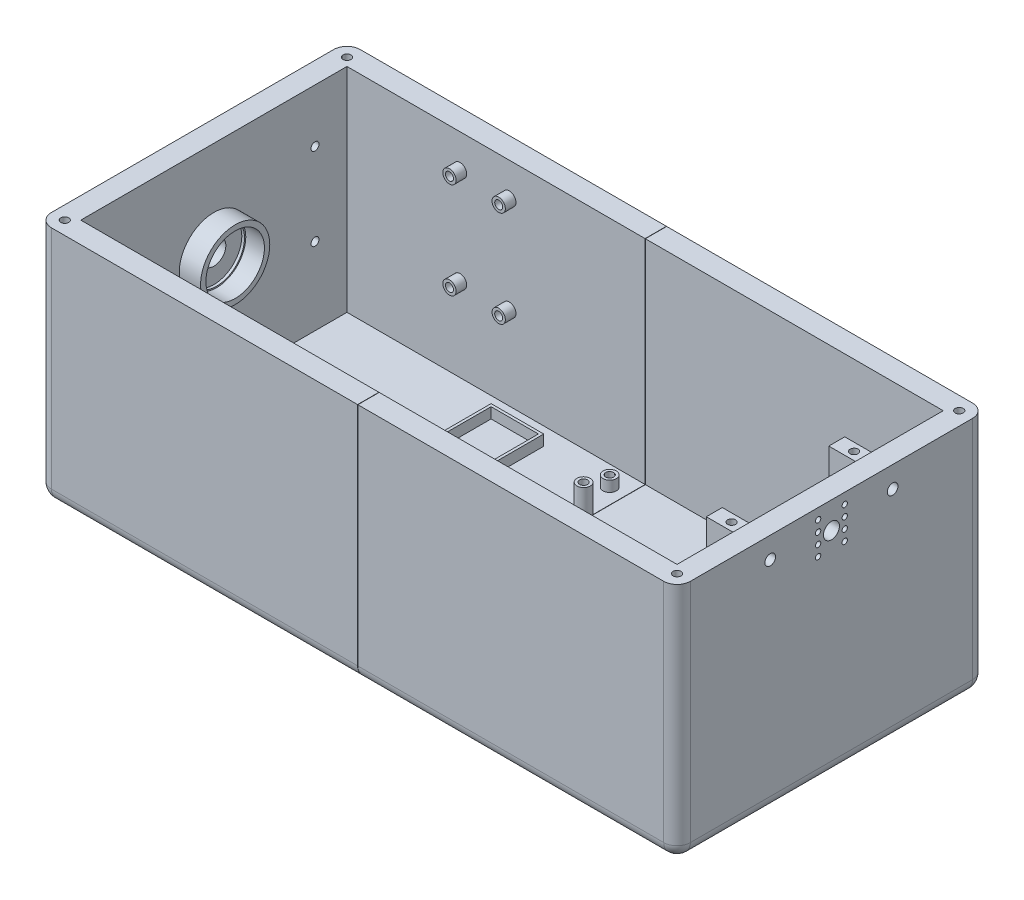
SolidWorks part; units mm, degrees
ref_plane "Front Plane" through (0, 0, 0) normal (0, 0, 1) x (1, 0, 0)
ref_plane "Top Plane" through (0, 0, 0) normal (0, 1, 0) x (1, 0, 0)
ref_plane "Right Plane" through (0, 0, 0) normal (1, 0, 0) x (0, 0, -1)
sketch "Sketch1" plane through (0, 0, 0) normal (0, 1, 0) x (1, 0, 0)
  line L1 (-120, 58) -> (120, 58)
  line L2 (-120, 58) -> (-120, -58)
  line L3 (-120, -58) -> (120, -58)
  line L4 (120, 58) -> (120, -58)
  line L5 (-120, 58) -> (120, -58) construction
  line L6 (-120, -58) -> (120, 58) construction
  point P0 (0, 0)
  dimension "D1" = 240
  dimension "D2" = 116
extrude "Boss-Extrude1" add sketch "Sketch1" along normal blind 10
sketch "Sketch2" plane through (0, 0, 0) normal (0, -1, 0) x (1, 0, 0)
  line L1 (-31.075, 31.075) -> (31.075, 31.075)
  line L2 (-31.075, 31.075) -> (-31.075, -31.075)
  line L3 (-31.075, -31.075) -> (31.075, -31.075)
  line L4 (31.075, 31.075) -> (31.075, -31.075)
  line L5 (-31.075, 31.075) -> (31.075, -31.075) construction
  line L6 (-31.075, -31.075) -> (31.075, 31.075) construction
  point P0 (0, 0)
  dimension "D1" = 62.15
  dimension "D2" = 62.15
extrude "Cut-Extrude1" cut sketch "Sketch2" against normal blind 2.5
sketch "Sketch3" plane through (0, 2.5, 0) normal (0, -1, 0) x (1, 0, 0)
  line L0 (0, 31.075) -> (0, -31.075) construction
  line L1 (31.075, 31.075) -> (-31.075, 31.075) construction
  line L2 (-31.075, -31.075) -> (31.075, -31.075) construction
  line L3 (-31.075, 0) -> (31.075, 0) construction
  line L4 (-31.075, 31.075) -> (-31.075, -31.075) construction
  line L5 (31.075, -31.075) -> (31.075, 31.075) construction
  line L6 (31.075, 31.075) -> (-31.075, 31.075) construction
  line L7 (-31.075, 31.075) -> (-31.075, -31.075) construction
  circle A0 centre (-26.075, 26.075) radius 1.5
  circle A1 centre (-26.075, -26.075) radius 1.5
  circle A2 centre (26.075, -26.075) radius 1.5
  circle A3 centre (26.075, 26.075) radius 1.5
  dimension "D1" = 3
  dimension "D3" = 5
  dimension "D2" = 5
extrude "Cut-Extrude2" cut sketch "Sketch3" against normal up to next
sketch "Sketch4" plane through (0, 0, 0) normal (0, -1, 0) x (1, 0, 0)
  line L0 (120, 58) -> (120, -58) construction
  line L1 (48, 7.75) -> (60, 7.75)
  line L2 (48, 7.75) -> (48, -7.75)
  line L3 (48, -7.75) -> (60, -7.75)
  line L4 (60, 7.75) -> (60, -7.75)
  line L5 (48, 7.75) -> (60, -7.75) construction
  line L6 (48, -7.75) -> (60, 7.75) construction
  point P0 (54, 0)
  dimension "D1" = 12
  dimension "D2" = 15.5
  dimension "D3" = 60
extrude "Cut-Extrude3" cut sketch "Sketch4" against normal blind 2.5
sketch "Sketch6" plane through (0, 2.5, 0) normal (0, -1, 0) x (1, 0, 0)
  line L0 (60, -7.75) -> (60, 7.75) construction
  line L1 (60, 7.75) -> (48, 7.75) construction
  line L2 (48, -7.75) -> (60, -7.75) construction
  circle A0 centre (58, 5.75) radius 1.5
  circle A1 centre (58, -5.75) radius 1.5
  dimension "D1" = 3
  dimension "D2" = 3
  dimension "D3" = 2
  dimension "D4" = 2
  dimension "D5" = 2
  dimension "D6" = 2
extrude "Cut-Extrude4" cut sketch "Sketch6" against normal up to next and the other way through all
sketch "Sketch7" plane through (0, 2.5, 0) normal (0, -1, 0) x (1, 0, 0)
  line L0 (48, -7.75) -> (60, -7.75) construction
  line L1 (48, 7.75) -> (54, 7.75)
  line L2 (48, 7.75) -> (48, -7.75)
  line L3 (48, -7.75) -> (54, -7.75)
  line L4 (54, 7.75) -> (54, -7.75)
extrude "Cut-Extrude5" cut sketch "Sketch7" against normal up to next
sketch "Sketch8" plane through (0, 10, 0) normal (0, 1, 0) x (1, 0, 0)
  line L1 (1.2, 26.7) -> (100, 26.7) construction
  line L2 (1.2, 26.7) -> (1.2, -26.7) construction
  line L3 (1.2, -26.7) -> (100, -26.7) construction
  line L4 (100, 26.7) -> (100, -26.7) construction
  line L5 (1.2, 26.7) -> (100, -26.7) construction
  line L6 (1.2, -26.7) -> (100, 26.7) construction
  line L11 (120, -58) -> (120, 58) construction
  line L15 (-120, -58) -> (120, -58) construction
  circle A0 centre (2.7, 24.2) radius 1.5
  circle A1 centre (9.7, -24.2) radius 1.5
  circle A2 centre (86.5, 24.2) radius 1.5
  circle A3 centre (84.5, -24.2) radius 1.5
  circle A4 centre (86.5, 24.2) radius 2.5
  circle A5 centre (84.5, -24.2) radius 2.3473
  circle A6 centre (9.7, -24.2) radius 2.5
  circle A7 centre (2.7, 24.2) radius 2.5
  point P0 (50.6, 0)
  dimension "D7" = 3
  dimension "D8" = 3
  dimension "D9" = 3
  dimension "D10" = 3
  dimension "D11" = 2.5
  dimension "D13" = 8.5
  dimension "D14" = 2.5
  dimension "D12" = 15.5
  dimension "D16" = 13.5
  dimension "D17" = 2.5
  dimension "D18" = 5
  dimension "D19" = 5
  dimension "D20" = 5
  dimension "D1" = 98.8
  dimension "D2" = 53.4
  dimension "D3" = 20
  dimension "D4" = 58
  dimension "D15" = 2.5
extrude "Boss-Extrude2" add sketch "Sketch8" along normal blind 15
sketch "Sketch9" plane through (0, 10, 0) normal (0, 1, 0) x (1, 0, 0)
  line L0 (-0.3, 58) -> (-0.3, -58) construction
  line L1 (-25.6, 47) -> (-4.3, 47) construction
  line L2 (-25.6, 47) -> (-25.6, 8.5) construction
  line L3 (-25.6, 8.5) -> (-4.3, 8.5) construction
  line L4 (-4.3, 47) -> (-4.3, 8.5) construction
  line L5 (-25.6, 47) -> (-4.3, 8.5) construction
  line L6 (-25.6, 8.5) -> (-4.3, 47) construction
  line L7 (-53.1, 47) -> (-29.6, 47) construction
  line L8 (-53.1, 47) -> (-53.1, 5) construction
  line L9 (-53.1, 5) -> (-29.6, 5) construction
  line L10 (-29.6, 47) -> (-29.6, 5) construction
  line L11 (-53.1, 47) -> (-29.6, 5) construction
  line L12 (-53.1, 5) -> (-29.6, 47) construction
  line L13 (120, 58) -> (-120, 58) construction
  line L14 (-120, -58) -> (120, -58) construction
  line L15 (-76.2, -9.5) -> (-54.9, -9.5) construction
  line L16 (-103.7, -9) -> (-80.2, -9) construction
  line L17 (-17.7, -47) -> (-17.7, -48)
  line L18 (-21.7, -23.8) -> (-4.3, -23.8)
  line L19 (-21.7, -23.8) -> (-21.7, -47)
  line L20 (-21.7, -47) -> (-17.7, -47)
  line L21 (-4.3, -23.8) -> (-4.3, -47)
  line L22 (-21.7, -23.8) -> (-4.3, -47) construction
  line L23 (-21.7, -47) -> (-4.3, -23.8) construction
  line L24 (-22.7, -22.8) -> (-3.3, -22.8)
  line L25 (-22.7, -22.8) -> (-22.7, -48)
  line L26 (-22.7, -48) -> (-17.7, -48)
  line L27 (-3.3, -22.8) -> (-3.3, -48)
  line L28 (-22.7, -22.8) -> (-3.3, -48) construction
  line L29 (-22.7, -48) -> (-3.3, -22.8) construction
  line L30 (-8.3, -47) -> (-8.3, -48)
  line L31 (-8.3, -47) -> (-4.3, -47)
  line L32 (-8.3, -48) -> (-3.3, -48)
  line L51 (-31.46, 43.383) -> (-31.46, 8.617)
  line L52 (-50.24, 42.383) -> (-32.46, 42.383)
  line L53 (-50.24, 42.383) -> (-50.24, 9.617)
  line L54 (-50.24, 9.617) -> (-32.46, 9.617)
  line L67 (31.45, 58) -> (31.45, -58) construction
  line L102 (-32.46, 42.383) -> (-32.46, 9.617)
  line L103 (-50.24, 42.383) -> (-32.46, 9.617) construction
  line L104 (-50.24, 9.617) -> (-32.46, 42.383) construction
  line L105 (-51.24, 8.617) -> (-31.46, 8.617)
  line L106 (-51.24, 43.383) -> (-51.24, 8.617)
  line L107 (-51.24, 43.383) -> (-31.46, 43.383)
  circle A0 centre (2.7, 24.2) radius 1.5 construction
  circle A1 centre (-5.8, 42.5) radius 1.5
  circle A2 centre (-5.8, 15.8) radius 1.5
  circle A3 centre (-24.1, 15.8) radius 1.5
  circle A4 centre (-24.1, 15.8) radius 2.5
  circle A5 centre (-5.8, 15.8) radius 2.5
  circle A6 centre (-5.8, 42.5) radius 2.5
  circle A7 centre (-50.6, 44.5) radius 1.5 construction
  circle A8 centre (-32.1, 44.5) radius 1.5 construction
  circle A9 centre (-32.1, 7.5) radius 1.5 construction
  circle A10 centre (-50.6, 7.5) radius 1.5 construction
  circle A11 centre (-50.6, 7.5) radius 2.5 construction
  circle A12 centre (-32.1, 7.5) radius 2.5 construction
  circle A13 centre (-32.1, 44.5) radius 2.5 construction
  circle A14 centre (-50.6, 44.5) radius 2.5 construction
  point P0 (-14.95, 27.75)
  point P5 (-41.35, 26)
  point P20 (-13, -35.4)
  point P27 (-13, -35.4)
  point P53 (-41.35, 26)
  dimension "D23" = 3
  dimension "D24" = 3
  dimension "D25" = 3
  dimension "D28" = 5
  dimension "D29" = 5
  dimension "D30" = 5
  dimension "D31" = 3
  dimension "D32" = 3
  dimension "D33" = 3
  dimension "D34" = 3
  dimension "D43" = 5
  dimension "D44" = 5
  dimension "D45" = 5
  dimension "D46" = 5
  dimension "D1" = 38.5
  dimension "D2" = 21.3
  dimension "D3" = 3
  dimension "D4" = 4
  dimension "D5" = 18
  dimension "D6" = 42
  dimension "D7" = 23.5
  dimension "D8" = 4
  dimension "D9" = 11
  dimension "D10" = 14
  dimension "D11" = 17.4
  dimension "D12" = 23.2
  dimension "D14" = 4
  dimension "D15" = 25.2
  dimension "D16" = 19.4
  dimension "D17" = 4
  dimension "D22" = 4.5
  dimension "D26" = 7.3
  dimension "D27" = 7.3
  dimension "D35" = 2.5
  dimension "D36" = 2.5
  dimension "D37" = 2.5
  dimension "D38" = 2.5
  dimension "D39" = 2.5
  dimension "D40" = 2.5
  dimension "D41" = 2.5
  dimension "D42" = 2.5
  dimension "D47" = 32.766
  dimension "D48" = 17.78
  dimension "D49" = 1
extrude "Boss-Extrude3" add sketch "Sketch9" along normal blind 4
sketch "Sketch10" plane through (0, 10, 0) normal (0, 1, 0) x (1, 0, 0)
  line L0 (-112, 50) -> (112, 50)
  line L1 (-120, 58) -> (120, 58)
  line L2 (-120, 58) -> (-120, -58)
  line L3 (-120, -58) -> (120, -58)
  line L4 (120, 58) -> (120, -58)
  line L5 (-120, 58) -> (120, -58) construction
  line L6 (-120, -58) -> (120, 58) construction
  line L7 (112, 50) -> (112, -50)
  line L8 (-112, -50) -> (112, -50)
  line L9 (-112, 50) -> (-112, -50)
  point P0 (0, 0)
  dimension "D1" = 8
extrude "Boss-Extrude4" add sketch "Sketch10" along normal blind 80
sketch "Sketch11" plane through (112, 0, 0) normal (-1, 0, 0) x (0, 0, 1)
  line L0 (-50, 90) -> (-50, 10) construction
  line L1 (-37, 82.5) -> (23, 82.5) construction
  line L2 (-37, 82.5) -> (-37, 17.5) construction
  line L3 (-37, 17.5) -> (23, 17.5) construction
  line L4 (23, 82.5) -> (23, 17.5) construction
  line L5 (-37, 82.5) -> (23, 17.5) construction
  line L6 (-37, 17.5) -> (23, 82.5) construction
  line L7 (-27.9, 70.9) -> (13.9, 70.9) construction
  line L8 (-27.9, 70.9) -> (-27.9, 29.1) construction
  line L9 (-27.9, 29.1) -> (13.9, 29.1) construction
  line L10 (13.9, 70.9) -> (13.9, 29.1) construction
  line L11 (-27.9, 70.9) -> (13.9, 29.1) construction
  line L12 (-27.9, 29.1) -> (13.9, 70.9) construction
  line L15 (50, 90) -> (-50, 90) construction
  circle A0 centre (-22.9, 65.9) radius 1.5
  circle A1 centre (8.9, 65.9) radius 1.5
  circle A2 centre (8.9, 34.1) radius 1.5
  circle A3 centre (-22.9, 34.1) radius 1.5
  circle A4 centre (-7, 67.5) radius 4.5
  point P0 (-7, 50)
  point P6 (-7, 50)
  dimension "D5" = 3
  dimension "D6" = 3
  dimension "D8" = 3
  dimension "D7" = 3
  dimension "D19" = 9
  dimension "D1" = 65
  dimension "D2" = 60
  dimension "D3" = 41.8
  dimension "D4" = 41.8
  dimension "D10" = 5
  dimension "D11" = 5
  dimension "D12" = 5
  dimension "D13" = 5
  dimension "D14" = 5
  dimension "D15" = 5
  dimension "D16" = 5
  dimension "D17" = 43
  dimension "D18" = 40
  dimension "D20" = 15
  dimension "D21" = 30
  dimension "D9" = 5
extrude "Cut-Extrude6" [suppressed] cut sketch "Sketch11" against normal up to next contours A1 | A3 | A2 | A0
sketch "Sketch13" [suppressed] plane through (120, 0, 0) normal (1, 0, 0) x (0, 0, -1)
  circle A0 centre (-8.9, 65.9) radius 3
  circle A1 centre (22.9, 65.9) radius 3
  circle A2 centre (22.9, 34.1) radius 3
  circle A3 centre (-8.9, 34.1) radius 3
  dimension "D1" = 6
  dimension "D2" = 6
  dimension "D3" = 6
  dimension "D4" = 6
extrude "Cut-Extrude7" [suppressed] cut sketch "Sketch13" against normal blind 4
sketch "Sketch24" plane through (-112, 0, 0) normal (1, 0, 0) x (0, 0, -1)
  line L0 (50, 10) -> (-50, 10) construction
  line L1 (-43, 34) -> (43, 34) construction
  line L2 (-43, 34) -> (-43, 75) construction
  line L3 (-43, 75) -> (43, 75) construction
  line L4 (43, 34) -> (43, 75) construction
  line L5 (-43, 34) -> (43, 75) construction
  line L6 (-43, 75) -> (43, 34) construction
  line L7 (50, 90) -> (-50, 90) construction
  line L8 (0, 75) -> (0, 34) construction
  circle A0 centre (-38, 70) radius 1.5
  circle A1 centre (-38, 39) radius 1.5
  circle A2 centre (38, 39) radius 1.5
  circle A3 centre (38, 70) radius 1.5
  point P0 (0, 54.5)
  point P9 (0, 10)
  dimension "D4" = 3
  dimension "D5" = 3
  dimension "D6" = 5
  dimension "D7" = 5
  dimension "D8" = 5
  dimension "D9" = 5
  dimension "D1" = 86
  dimension "D2" = 41
  dimension "D3" = 15
extrude "Cut-Extrude14" cut sketch "Sketch24" against normal up to next
sketch "Sketch14" plane through (-112, 0, 0) normal (1, 0, 0) x (0, 0, -1)
  circle A0 centre (0, 54.5) radius 13
  circle A2 centre (0, 54.5) radius 11
  dimension "D1" = 26
  dimension "D2" = 22
  dimension "D3" = 0
extrude "Boss-Extrude6" add sketch "Sketch14" along normal blind 8
sketch "Sketch16" plane through (-112, 0, 0) normal (1, 0, 0) x (0, 0, -1)
  circle A0 centre (0, 54.5) radius 10.5
  circle A1 centre (0, 54.5) radius 11
  dimension "D1" = 21
  dimension "D2" = 22
extrude "Boss-Extrude7" add sketch "Sketch16" along normal blind 1
sketch "Sketch18" plane through (0, 0, -50) normal (0, 0, 1) x (1, 0, 0)
  line L0 (-60.25, 80) -> (-60.25, 38) construction
  line L1 (-72, 80) -> (-48.5, 80) construction
  line L2 (-72, 80) -> (-72, 38) construction
  line L3 (-72, 38) -> (-48.5, 38) construction
  line L4 (-48.5, 80) -> (-48.5, 38) construction
  line L5 (-72, 80) -> (-48.5, 38) construction
  line L6 (-72, 38) -> (-48.5, 80) construction
  line L7 (-72, 59.4256) -> (-48.5, 59.4256) construction
  line L8 (112, 90) -> (-112, 90) construction
  line L9 (-112, 90) -> (-112, 10) construction
  circle A0 centre (-69.5, 77.5) radius 1.5
  circle A1 centre (-69.5, 77.5) radius 2.5
  circle A2 centre (-69.5, 41.3512) radius 1.5
  circle A3 centre (-69.5, 41.3512) radius 2.5
  circle A4 centre (-51, 41.3512) radius 2.5
  circle A5 centre (-51, 41.3512) radius 1.5
  circle A6 centre (-51, 77.5) radius 2.5
  circle A7 centre (-51, 77.5) radius 1.5
  point P0 (-60.25, 59)
  dimension "D3" = 3
  dimension "D4" = 5
  dimension "D5" = 2.5
  dimension "D6" = 2.5
  dimension "D1" = 42
  dimension "D2" = 23.5
  dimension "D7" = 10
  dimension "D8" = 40
sketch "Sketch17" plane through (-112, 0, 0) normal (1, 0, 0) x (0, 0, -1)
  circle A0 centre (0, 54.5) radius 4.5
  dimension "D1" = 9
extrude "Cut-Extrude9" cut sketch "Sketch17" against normal up to next
extrude "Boss-Extrude8" add sketch "Sketch18" along normal blind 4
fillet "Fillet1" radius 5 8 edges at (120, 45, -58) (-120, 45, -58) (0, 0, -58) (-120, 0, 0) (0, 0, 58) (-120, 45, 58) (120, 0, 0) (120, 45, 58)
sketch "Sketch19" plane through (0, 90, 0) normal (0, 1, 0) x (1, 0, 0)
  circle A3 centre (115, 53) radius 1.5
  circle A4 centre (-115, 53) radius 1.5
  circle A5 centre (-115, -53) radius 1.5
  circle A6 centre (115, -53) radius 1.5
  dimension "D1" = 3
  dimension "D2" = 3
  dimension "D3" = 3
  dimension "D4" = 3
extrude "Cut-Extrude10" cut sketch "Sketch19" against normal blind 20
sketch "Sketch20" plane through (120, 0, 0) normal (1, 0, 0) x (0, 0, -1)
  line L0 (0, 90) -> (0, 0) construction
  line L1 (-53, 90) -> (53, 90) construction
  circle A0 centre (-23, 82) radius 2
  circle A1 centre (23, 82) radius 2
  dimension "D1" = 23
  dimension "D2" = 4
  dimension "D3" = 8
extrude "Cut-Extrude11" cut sketch "Sketch20" against normal up to next
sketch "Sketch21" plane through (112, 0, 0) normal (-1, 0, 0) x (0, 0, 1)
  line L1 (-26, 87) -> (-20, 87)
  line L2 (-26, 87) -> (-26, 77)
  line L3 (-26, 77) -> (-20, 77)
  line L4 (-20, 87) -> (-20, 77)
  line L5 (-26, 87) -> (-20, 77) construction
  line L6 (-26, 77) -> (-20, 87) construction
  line L7 (20, 87) -> (26, 87)
  line L8 (20, 87) -> (20, 77)
  line L9 (20, 77) -> (26, 77)
  line L10 (26, 87) -> (26, 77)
  line L11 (20, 87) -> (26, 77) construction
  line L12 (20, 77) -> (26, 87) construction
  circle A0 centre (23, 82) radius 2
  circle A1 centre (-23, 82) radius 2
  point P0 (-23, 82)
  point P6 (23, 82)
  dimension "D5" = 4
  dimension "D6" = 4
  dimension "D1" = 6
  dimension "D2" = 6
  dimension "D3" = 10
  dimension "D4" = 10
extrude "Boss-Extrude9" add sketch "Sketch21" along normal blind 13
sketch "Sketch22" plane through (0, 87, 0) normal (0, 1, 0) x (1, 0, 0)
  line L0 (99, -26) -> (99, -20) construction
  line L1 (99, -20) -> (112, -20) construction
  line L2 (99, 20) -> (99, 26) construction
  line L3 (99, 26) -> (112, 26) construction
  circle A0 centre (105.5, -23) radius 1.5
  circle A1 centre (105.5, 23) radius 1.5
  dimension "D1" = 3
  dimension "D2" = 6.5
  dimension "D3" = 3
  dimension "D4" = 3
  dimension "D5" = 6.5
  dimension "D6" = 3
extrude "Cut-Extrude12" cut sketch "Sketch22" against normal up to next
sketch "Sketch23" plane through (120, 0, 0) normal (1, 0, 0) x (0, 0, -1)
  line L0 (0, 90) -> (0, 5) construction
  line L1 (-53, 90) -> (53, 90) construction
  line L2 (-53, 5) -> (53, 5) construction
  line L3 (-9.0972, 80) -> (9.0972, 80) construction
  circle A0 centre (5, 78) radius 1
  circle A1 centre (-5, 78) radius 1
  circle A2 centre (5, 74) radius 1
  circle A3 centre (-5, 74) radius 1
  circle A4 centre (-5, 86) radius 1
  circle A5 centre (5, 86) radius 1
  circle A6 centre (-5, 82) radius 1
  circle A7 centre (5, 82) radius 1
  circle A8 centre (0, 80) radius 3
  point P24 (0, 80)
  dimension "D1" = 2
  dimension "D2" = 2
  dimension "D3" = 5
  dimension "D4" = 5
  dimension "D5" = 12
  dimension "D6" = 12
  dimension "D7" = 2
  dimension "D8" = 2
  dimension "D9" = 5
  dimension "D10" = 5
  dimension "D11" = 4
  dimension "D12" = 4
  dimension "D13" = 2
  dimension "D14" = 6
extrude "Cut-Extrude13" cut sketch "Sketch23" against normal up to next
ref_plane "Plane1" through (-120, 0, 0) normal (-1, 0, 0) x (0, 0, 1)
sketch "Sketch25" plane through (-120, 0, 0) normal (-1, 0, 0) x (0, 0, 1)
  line L0 (-53, 90) -> (-53, 5)
  line L1 (53, 5) -> (53, 90)
  line L2 (-53, 90) -> (53, 90)
  line L3 (-53, 5) -> (53, 5)
  line L4 (-53, 5) -> (53, 5)
  line L5 (-53, 90) -> (53, 90)
  line L6 (53, 5) -> (53, 90)
  line L7 (-53, 90) -> (-53, 5)
  circle A0 centre (0, 54.5) radius 4.5
  circle A1 centre (38, 70) radius 1.5
  circle A2 centre (-38, 39) radius 1.5
  circle A3 centre (-38, 70) radius 1.5
  circle A4 centre (38, 39) radius 1.5
  circle A5 centre (38, 39) radius 1.5
  circle A6 centre (-38, 70) radius 1.5
  circle A7 centre (-38, 39) radius 1.5
  circle A8 centre (38, 70) radius 1.5
  circle A9 centre (0, 54.5) radius 4.5
ref_plane "Plane2" through (0, 0, 0) normal (-1, 0, 0) x (0, 0, 1)
sketch "Sketch26" plane through (0, 0, 0) normal (-1, 0, 0) x (0, 0, 1)
  line L0 (-31.075, 0.75) -> (-55.6339, 0.75)
  line L1 (55.6339, 0.75) -> (31.075, 0.75)
  line L2 (-50, 10) -> (-50, 90)
  line L3 (50, 90) -> (50, 10)
  line L4 (-50, 90) -> (-58, 90)
  line L5 (58, 90) -> (50, 90)
  line L6 (-31.075, 2.5) -> (31.075, 2.5)
  line L7 (58, 90) -> (58, 5)
  line L8 (-58, 5) -> (-58, 90)
  line L9 (50, 10) -> (-50, 10)
  line L10 (31.075, 0.75) -> (31.075, 2.5)
  line L11 (-31.075, 2.5) -> (-31.075, 0.75)
  line L12 (-31.075, 2.5) -> (-31.075, 0.75)
  line L13 (31.075, 0.75) -> (31.075, 2.5)
  line L14 (50, 10) -> (-50, 10)
  line L15 (-58, 5) -> (-58, 90)
  line L16 (58, 90) -> (58, 5)
  line L17 (-31.075, 2.5) -> (31.075, 2.5)
  line L18 (58, 90) -> (50, 90)
  line L19 (-50, 90) -> (-58, 90)
  line L20 (50, 90) -> (50, 10)
  line L21 (-50, 10) -> (-50, 90)
  line L22 (55.6339, 0.75) -> (31.075, 0.75)
  line L23 (-31.075, 0.75) -> (-55.6339, 0.75)
  arc A0 (-58, 5) -> (-55.6339, 0.75) centre (-53, 5) ccw
  arc A1 (55.6339, 0.75) -> (58, 5) centre (53, 5) ccw
  arc A2 (55.6339, 0.75) -> (58, 5) centre (53, 5) ccw
  arc A3 (-58, 5) -> (-55.6339, 0.75) centre (-53, 5) ccw
sketch "Sketch27" plane through (0, 0, 0) normal (-1, 0, 0) x (0, 0, 1)
  line L1 (-68.0376, 113.8657) -> (68.0376, 113.8657)
  line L2 (-68.0376, 113.8657) -> (-68.0376, -4.8657)
  line L3 (-68.0376, -4.8657) -> (68.0376, -4.8657)
  line L4 (68.0376, 113.8657) -> (68.0376, -4.8657)
  line L5 (-68.0376, 113.8657) -> (68.0376, -4.8657) construction
  line L6 (-68.0376, -4.8657) -> (68.0376, 113.8657) construction
  point P0 (0, 54.5)
extrude "Cut-Extrude15" cut sketch "Sketch27" against normal blind 0.1
sketch "Sketch29" plane through (0.1, 0, 0) normal (-1, 0, 0) x (0, 0, 1)
  line L0 (31.075, 0) -> (53, 0) construction
  line L1 (58, 90) -> (58, 5) construction
  line L2 (-53, 0) -> (-31.075, 0) construction
  line L3 (-58, 5) -> (-58, 90) construction
  circle A0 centre (-48, 4) radius 2.25
  circle A1 centre (48, 4) radius 2.25
  dimension "D1" = 4.5
  dimension "D2" = 4.5
  dimension "D3" = 4
  dimension "D4" = 10
  dimension "D5" = 4
  dimension "D6" = 10
extrude "Cut-Extrude16" cut sketch "Sketch29" against normal blind 100
equation "\"D2@Sketch2\"=\"D1@Sketch2\""
equation "\"D15@Sketch9\"=\"D12@Sketch9\"+2"
equation "\"D16@Sketch9\"=\"D11@Sketch9\"+2"
equation "\"D17@Sketch11\"=86/2"
equation "\"D18@Sketch11\"=80/2"
